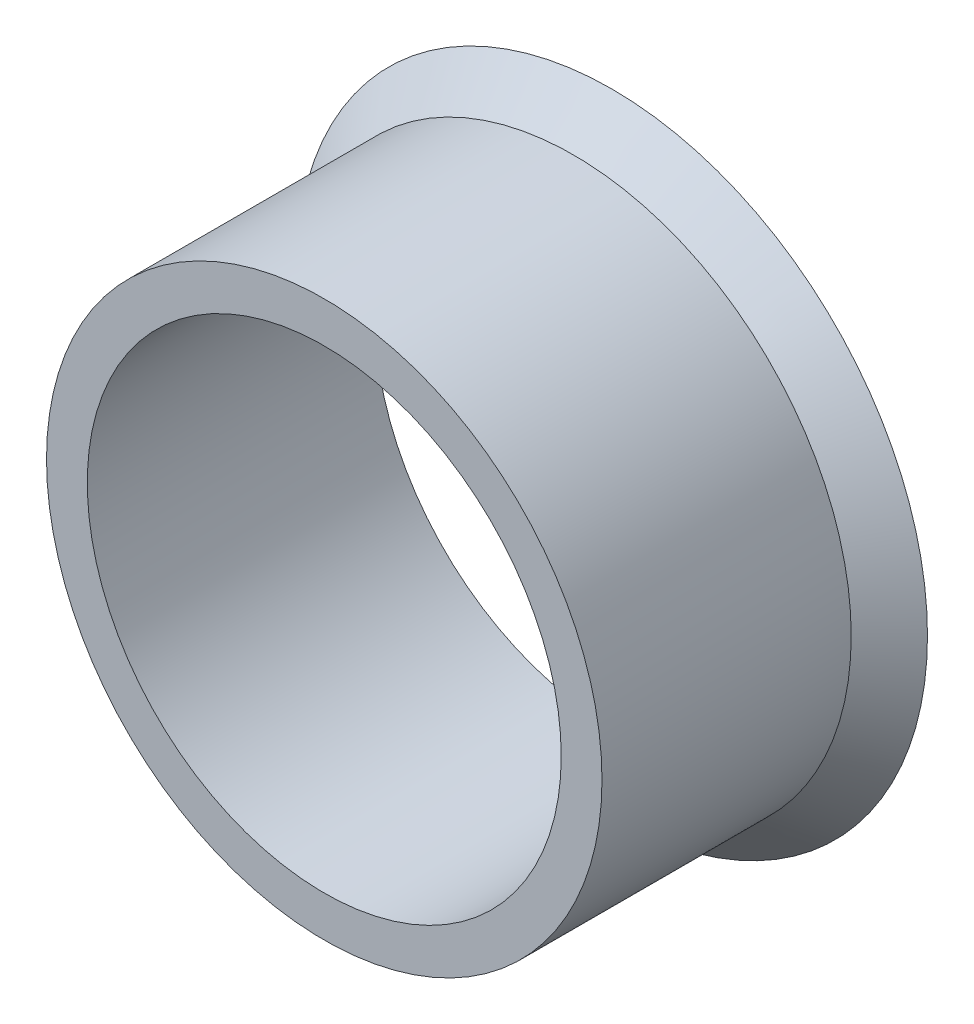
SolidWorks part; units mm, degrees
ref_plane "Ön Düzlem" through (0, 0, 0) normal (0, 0, 1) x (1, 0, 0)
ref_plane "Üst Düzlem" through (0, 0, 0) normal (0, 1, 0) x (1, 0, 0)
ref_plane "Sağ Düzlem" through (0, 0, 0) normal (1, 0, 0) x (0, 0, -1)
sketch "Çizim1" plane through (0, 0, 0) normal (0, 0, 1) x (1, 0, 0)
  circle A0 centre (0, 0) radius 27.1
  dimension "D2" = 54.2
extrude "Yükseklik-Ekstrüzyon1" add sketch "Çizim1" along normal blind 3.3
sketch "Çizim3" plane through (0, 0, 3.3) normal (0, 0, 1) x (1, 0, 0)
  circle A0 centre (0, 0) radius 23.85
  dimension "D1" = 47.7
extrude "Yükseklik-Ekstrüzyon2" add sketch "Çizim3" along normal blind 21.4
loft "Loft1" add section edge at (27.1, 0, 0) section edge at (23.85, 0, 3.3)
sketch "Çizim5" plane through (0, 0, 0) normal (0, 1, 0) x (1, 0, 0)
  line L0 (-27.1, 0) -> (-23.85, -3.3)
  line L1 (-23.85, -3.3) -> (-27.1, -3.3)
  line L2 (-27.1, -3.3) -> (-27.1, 0)
  line L3 (0, 4.7341) -> (0, -29.2004)
revolve "Kes-Döndür1" cut sketch "Çizim5" angle 360 about L3
sketch "Çizim6" plane through (0, 0, 24.7) normal (0, 0, 1) x (1, 0, 0)
  circle A0 centre (0, 0) radius 20.35
  dimension "D1" = 40.7
extrude "Kes-Ekstrüzyon1" cut sketch "Çizim6" against normal blind 50
